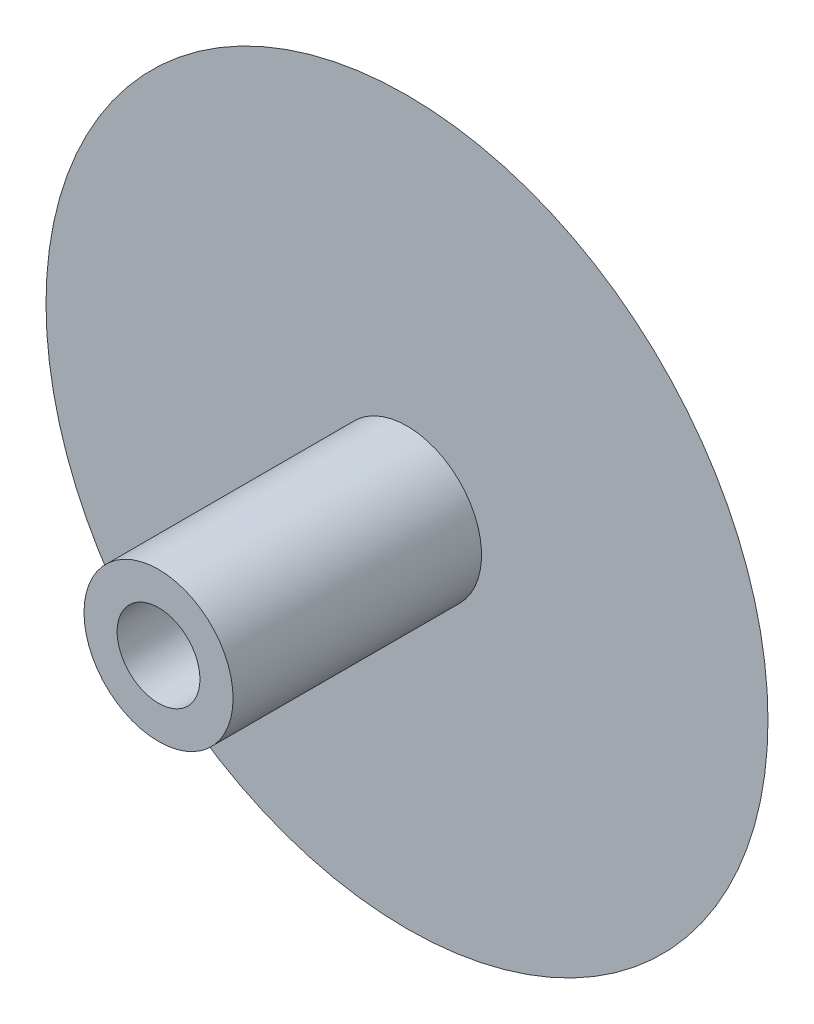
SolidWorks part; units mm, degrees
ref_plane "前基準面" through (0, 0, 0) normal (0, 0, 1) x (1, 0, 0)
ref_plane "上基準面" through (0, 0, 0) normal (0, 1, 0) x (1, 0, 0)
ref_plane "右基準面" through (0, 0, 0) normal (1, 0, 0) x (0, 0, -1)
sketch "草圖1" plane through (0, 0, 0) normal (0, 1, 0) x (1, 0, 0)
  line L0 (21.7945, 45) -> (0, 45)
  line L1 (0, 45) -> (0, 50)
  line L2 (0, 121.0943) -> (0, -75.854) construction
  arc A0 (21.7945, 45) -> (0, 50) centre (0, 0) ccw
  dimension "D1" = 50
  dimension "D2" = 0
  dimension "D3" = 45
revolve "旋轉1" add sketch "草圖1" angle 360 about L2
sketch "草圖2" plane through (0, 0, -45) normal (0, 0, 1) x (1, 0, 0)
  circle A0 centre (0, 0) radius 2.5
  circle A1 centre (0, 0) radius 4.5
  dimension "D1" = 5
  dimension "D2" = 9
extrude "填料-伸長1" add sketch "草圖2" along normal blind 15
